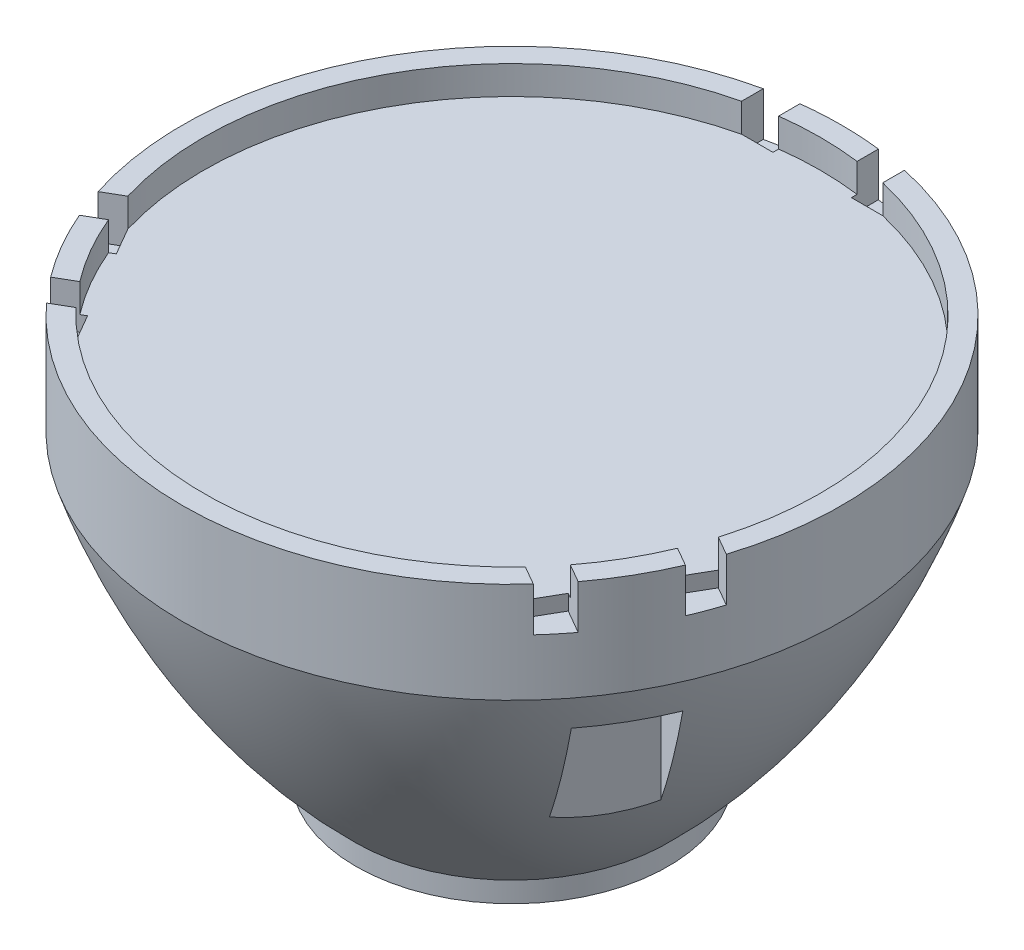
SolidWorks part; units mm, degrees
material "PMMA"
ref_plane "Front Plane" through (0, 0, 0) normal (0, 0, 1) x (1, 0, 0)
ref_plane "Top Plane" through (0, 0, 0) normal (0, 1, 0) x (1, 0, 0)
ref_plane "Right Plane" through (0, 0, 0) normal (1, 0, 0) x (0, 0, -1)
sketch "Sketch1" plane through (0, 0, 0) normal (0, 0, 1) x (1, 0, 0)
  line L0 (0, 0) -> (0, 5.7613) construction
  line L1 (0, 0) -> (4.975, 0)
  line L2 (4.975, 0) -> (4.975, 0.65)
  line L3 (10.5, 9.52) -> (10.5, 12.72)
  line L4 (10.5, 12.72) -> (0, 12.72)
  line L5 (0, 0) -> (0, 12.72)
  arc A0 (4.975, 0.65) -> (10.5, 9.52) centre (-10.4019, 16.3838) ccw
  dimension "D6" = 22
  dimension "D1" = 12.72
  dimension "D2" = 0.65
  dimension "D3" = 3.2
  dimension "D4" = 4.975
  dimension "D5" = 10.5
revolve "Lens Holder" add sketch "Sketch1" angle 360 about L0
sketch "Sketch3" plane through (0, 12.72, 0) normal (0, 1, 0) x (1, 0, 0)
  circle A0 centre (0, 0) radius 9.825
  dimension "D1" = 19.65
extrude "Lens Top Cut-Extrude2" cut sketch "Sketch3" against normal blind 0.91
sketch "Sketch2" plane through (0, 12.72, 0) normal (0, 1, 0) x (1, 0, 0)
  line L0 (0, 0) -> (0, 10.5) construction
  line L1 (8.4036, -6.2952) -> (7.9036, -7.1612)
  line L2 (1.25, 10.4253) -> (2.25, 10.4253)
  line L3 (1.25, 10.4253) -> (1.25, 9.5639)
  line L4 (1.25, 9.5639) -> (2.25, 9.5639)
  line L5 (2.25, 10.4253) -> (2.25, 9.5639)
  line L6 (-2.25, 10.4253) -> (-1.25, 10.4253)
  line L7 (-2.25, 10.4253) -> (-2.25, 9.5639)
  line L8 (-2.25, 9.5639) -> (-1.25, 9.5639)
  line L9 (-1.25, 10.4253) -> (-1.25, 9.5639)
  line L10 (7.9036, -7.1612) -> (7.1576, -6.7305)
  line L11 (7.6576, -5.8645) -> (7.1576, -6.7305)
  line L12 (8.4036, -6.2952) -> (7.6576, -5.8645)
  line L13 (10.1536, -3.2641) -> (9.6536, -4.1301)
  line L14 (9.4076, -2.8334) -> (8.9076, -3.6994)
  line L15 (9.6536, -4.1301) -> (8.9076, -3.6994)
  line L16 (10.1536, -3.2641) -> (9.4076, -2.8334)
  line L17 (-9.6536, -4.1301) -> (-10.1536, -3.2641)
  line L18 (-10.1536, -3.2641) -> (-9.4076, -2.8334)
  line L19 (-8.9076, -3.6994) -> (-9.4076, -2.8334)
  line L20 (-9.6536, -4.1301) -> (-8.9076, -3.6994)
  line L21 (-7.9036, -7.1612) -> (-8.4036, -6.2952)
  line L22 (-7.1576, -6.7305) -> (-7.6576, -5.8645)
  line L23 (-8.4036, -6.2952) -> (-7.6576, -5.8645)
  line L24 (-7.9036, -7.1612) -> (-7.1576, -6.7305)
  circle A0 centre (0, 0) radius 10.5 construction
  circle A1 centre (0, 0) radius 9.825 construction
  point P33 (0, 0)
  dimension "D1" = 1
  dimension "D2" = 4.5
  dimension "D3" = 3
extrude "Top Cut-Extrude3" cut sketch "Sketch2" against normal blind 1.4
sketch "Sketch4" plane through (0, 0, 0) normal (0, -1, 0) x (1, 0, 0)
  line L0 (2.49, 1.8) -> (1.99, 1.3)
  line L1 (-2.49, 2.49) -> (-1.8, 2.49)
  line L2 (-2.49, 2.49) -> (-2.49, 1.8)
  line L3 (-2.49, -2.49) -> (-1.8, -2.49)
  line L4 (2.49, 2.49) -> (2.49, 1.8)
  line L5 (1.99, 1.3) -> (2.49, 0.8)
  line L6 (0, 0) -> (2.49, 0) construction
  line L7 (1.99, -1.3) -> (2.49, -0.8)
  line L8 (2.49, -1.8) -> (1.99, -1.3)
  line L9 (2.49, 0.8) -> (2.49, -0.8)
  line L10 (2.49, -1.8) -> (2.49, -2.49)
  line L11 (-1.8, -2.49) -> (-1.3, -1.99)
  line L12 (-1.3, -1.99) -> (-0.8, -2.49)
  line L13 (1.3, -1.99) -> (0.8, -2.49)
  line L14 (1.8, -2.49) -> (1.3, -1.99)
  line L15 (-2.49, 1.8) -> (-1.99, 1.3)
  line L16 (-1.99, 1.3) -> (-2.49, 0.8)
  line L17 (-1.99, -1.3) -> (-2.49, -0.8)
  line L18 (-2.49, -1.8) -> (-1.99, -1.3)
  line L19 (1.8, 2.49) -> (1.3, 1.99)
  line L20 (1.3, 1.99) -> (0.8, 2.49)
  line L21 (-1.3, 1.99) -> (-0.8, 2.49)
  line L22 (-1.8, 2.49) -> (-1.3, 1.99)
  line L23 (1.8, -2.49) -> (2.49, -2.49)
  line L24 (-0.8, -2.49) -> (0.8, -2.49)
  line L25 (-2.49, -1.8) -> (-2.49, -2.49)
  line L26 (-2.49, 0.8) -> (-2.49, -0.8)
  line L27 (-0.8, 2.49) -> (0.8, 2.49)
  line L28 (1.8, 2.49) -> (2.49, 2.49)
  circle A0 centre (0, 0) radius 2.49 construction
  point P35 (0, 0)
  dimension "D1" = 4.98
  dimension "D2" = 1
  dimension "D3" = 0.5
  dimension "D4" = 2.6
  dimension "D5" = 4
extrude "Bottom Cut-Extrude4" cut sketch "Sketch4" against normal blind 0.8
ref_plane "Plane1" through (0, 9.52, 0) normal (0, 1, 0) x (1, 0, 0)
sketch "Sketch5" plane through (0, 9.52, 0) normal (0, 1, 0) x (1, 0, 0)
  line L0 (0, 0) -> (0, 10.5) construction
  line L1 (-1.3, 10.4192) -> (1.3, 10.4192) construction
  line L2 (-1.3, 10.016) -> (-1.3, 8.1)
  line L3 (-1.3, 8.1) -> (1.3, 8.1)
  line L4 (1.3, 10.016) -> (1.3, 8.1)
  line L5 (1.3, 10.016) -> (1.3, 10.4192) construction
  line L6 (-1.3, 10.016) -> (-1.3, 10.4192) construction
  line L7 (8.0241, -6.1338) -> (6.3648, -5.1758)
  line L8 (7.6648, -2.9242) -> (6.3648, -5.1758)
  line L9 (9.3241, -3.8822) -> (7.6648, -2.9242)
  line L10 (-9.3241, -3.8822) -> (-7.6648, -2.9242)
  line L11 (-6.3648, -5.1758) -> (-7.6648, -2.9242)
  line L12 (-8.0241, -6.1338) -> (-6.3648, -5.1758)
  circle A0 centre (0, 0) radius 10.5 construction
  arc A1 (-1.3, 10.016) -> (1.3, 10.016) centre (0, 0) cw
  arc A2 (9.3241, -3.8822) -> (8.0241, -6.1338) centre (0, 0) cw
  arc A3 (-8.0241, -6.1338) -> (-9.3241, -3.8822) centre (0, 0) cw
  point P22 (0, 0)
  dimension "D2" = 0.4
  dimension "D1" = 2.6
  dimension "D4" = 2.4
  dimension "D3" = 3
extrude "Side Cut-Extrude5" cut sketch "Sketch5" against normal blind 8
sketch "Sketch6" plane through (0, 0.8, 0) normal (0, -1, 0) x (1, 0, 0)
  circle A0 centre (0, 0) radius 2.6
  dimension "D1" = 5.2
extrude "Lens Hole Cut-Extrude7" cut sketch "Sketch6" against normal blind 5
equation "\"D4@Sketch1\"=9.95/2"
equation "\"D5@Sketch1\"=21/2"
